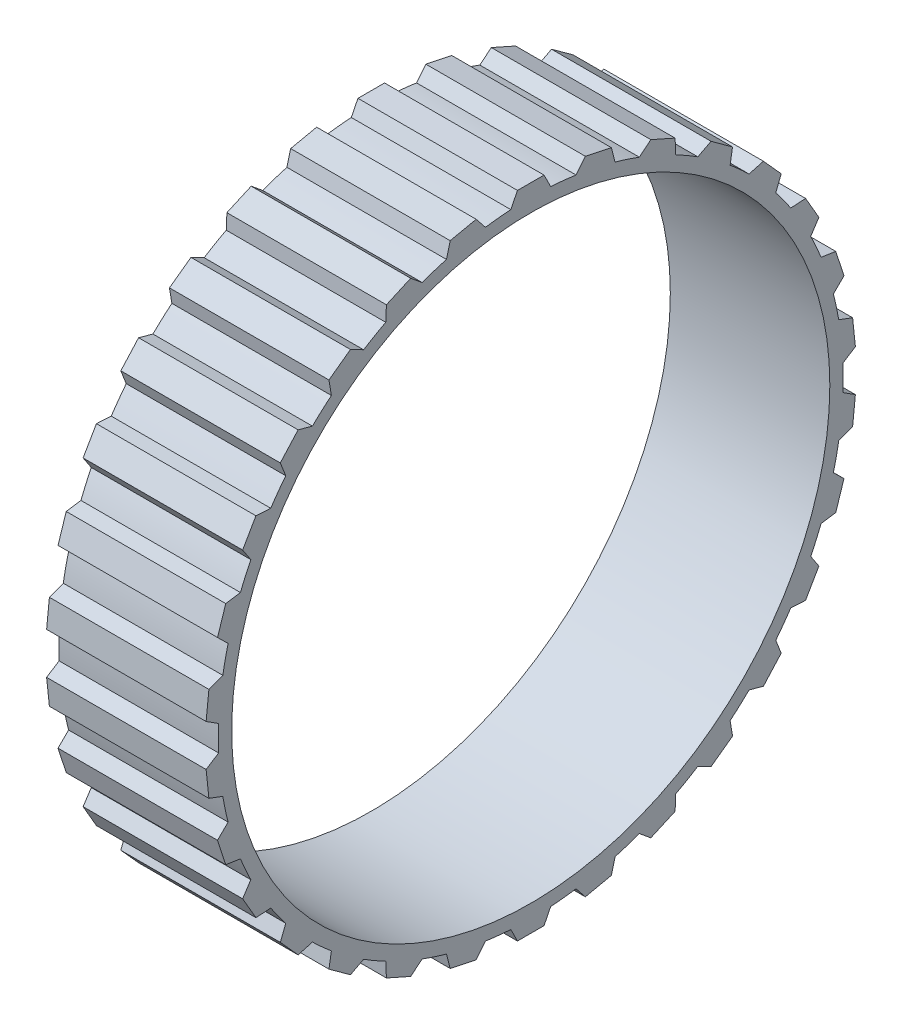
SolidWorks part; units mm, degrees
ref_plane "Front Plane" through (0, 0, 0) normal (0, 0, 1) x (1, 0, 0)
ref_plane "Top Plane" through (0, 0, 0) normal (0, 1, 0) x (1, 0, 0)
ref_plane "Right Plane" through (0, 0, 0) normal (1, 0, 0) x (0, 0, -1)
sketch "Sketch1" plane through (0, 0, 0) normal (1, 0, 0) x (0, 0, -1)
  circle A0 centre (0, 0) radius 22.5
  dimension "D1" = 45
extrude "Extrude-Thin1" add sketch "Sketch1" along normal blind 12 thin
sketch "Sketch3" plane through (0, 0, 0) normal (-1, 0, 0) x (0, 0, 1)
  line L0 (0, 29.526) -> (0, -30.1149) construction
  line L1 (-1, 24.4521) -> (1, 24.4521)
  line L2 (1, 24.4521) -> (1.5, 23.4521)
  line L3 (-1, 24.4521) -> (-1.5, 23.4521)
  line L4 (-1.5, 23.4521) -> (1.5, 23.4521)
  circle A0 centre (0, 0) radius 23.5 construction
  point P6 (0, 0)
  point P7 (0, 0)
  point P12 (0, 24.4521)
  dimension "D1" = 1
  dimension "D2" = 1.5
  dimension "D3" = 1
extrude "Boss-Extrude2" add sketch "Sketch3" against normal blind 12
pattern_circular "CirPattern4" count 30 over 360 about axis through (0, 0, 0) along (1, 0, 0) of "Boss-Extrude2"
